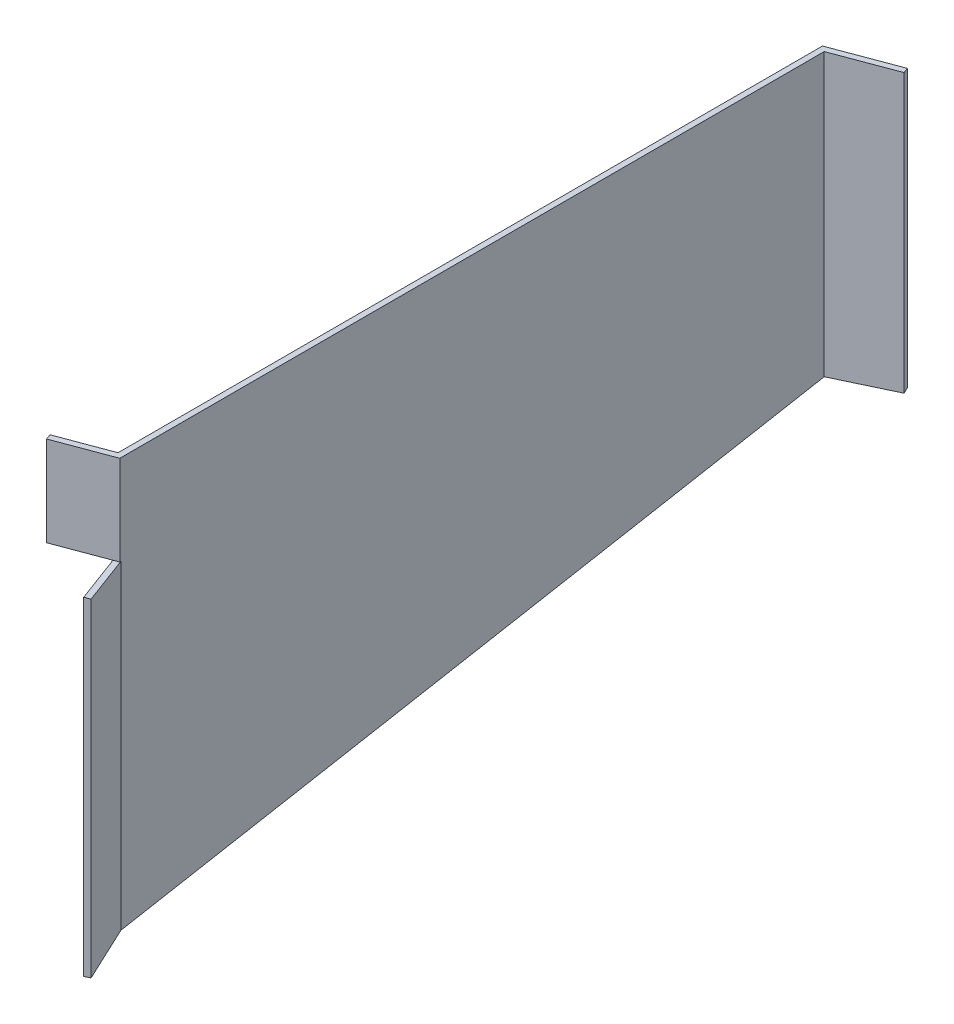
SolidWorks part; units mm, degrees
ref_plane "Front Plane" through (0, 0, 0) normal (0, 0, 1) x (1, 0, 0)
ref_plane "Top Plane" through (0, 0, 0) normal (0, 1, 0) x (1, 0, 0)
ref_plane "Right Plane" through (0, 0, 0) normal (1, 0, 0) x (0, 0, -1)
sketch "Sketch1" plane through (0, 0, 0) normal (0, 1, 0) x (1, 0, 0)
  line L1 (0, 0) -> (3.175, 0)
  line L2 (0, 0) -> (0, 395.4099)
  line L3 (0, 395.4099) -> (3.175, 395.4099)
  line L4 (3.175, 0) -> (3.175, 395.4099)
  dimension "D1" = 3.175
  dimension "D2" = 395.4099
extrude "Boss-Extrude1" add sketch "Sketch1" along normal blind 228.6
sketch "Sketch2" plane through (3.175, 0, 0) normal (1, 0, 0) x (0, 0, -1)
  line L0 (0, 0) -> (395.4099, 71.7959)
  line L1 (395.4099, 228.6) -> (395.4099, 0) construction
  line L2 (395.4099, 71.7959) -> (395.4099, 0)
  line L3 (395.4099, 0) -> (0, 0)
  dimension "D1" = 71.7959
extrude "Cut-Extrude1" cut sketch "Sketch2" against normal through all
ref_plane "Plane1" through (0, 228.6, -395.4099) normal (0, 0, 1) x (1, 0, 0)
sketch "Sketch8" plane through (0, 228.6, 0) normal (0, 1, 0) x (1, 0, 0)
  line L0 (0, 395.4099) -> (34.5021, 408.296)
  line L1 (34.5021, 408.296) -> (35.613, 405.3217)
  line L2 (35.613, 405.3217) -> (0, 392.0207)
  line L3 (0, 395.4099) -> (0, 0) construction
  line L4 (0, 392.0207) -> (0, 395.4099)
  dimension "D1" = 36.83
  dimension "D2" = 3.175
  dimension "D3" = 249.52
extrude "Boss-Extrude4" add sketch "Sketch8" against normal up to surface (157.4195 mm away)
sketch "Sketch9" plane through (0, 228.6, 0) normal (0, 1, 0) x (1, 0, 0)
  line L0 (3.175, 0) -> (-26.5682, -11.1087)
  line L1 (-26.5682, -11.1087) -> (-27.6791, -8.1344)
  line L2 (-27.6791, -8.1344) -> (3.175, 3.3892)
  line L3 (3.175, 0) -> (3.175, 393.2065) construction
  line L4 (3.175, 3.3892) -> (3.175, 0)
  dimension "D1" = 31.75
  dimension "D2" = 3.175
  dimension "D3" = 249.52
extrude "Boss-Extrude5" add sketch "Sketch9" against normal blind 50.165
sketch "Sketch13" plane through (0, 178.435, 0) normal (0, -1, 0) x (1, 0, 0)
  line L0 (0, 0) -> (10.1065, 27.0599)
  line L1 (10.1065, 27.0599) -> (13.0808, 25.949)
  line L2 (13.0808, 25.949) -> (1.9721, -3.7942)
  line L3 (-26.5682, 11.1087) -> (3.175, 0) construction
  line L4 (1.9721, -3.7942) -> (0, 0)
  dimension "D1" = 3.175
  dimension "D2" = 31.75
  dimension "D3" = 90
extrude "Boss-Extrude8" add sketch "Sketch13" along normal up to surface (177.7461 mm away)
